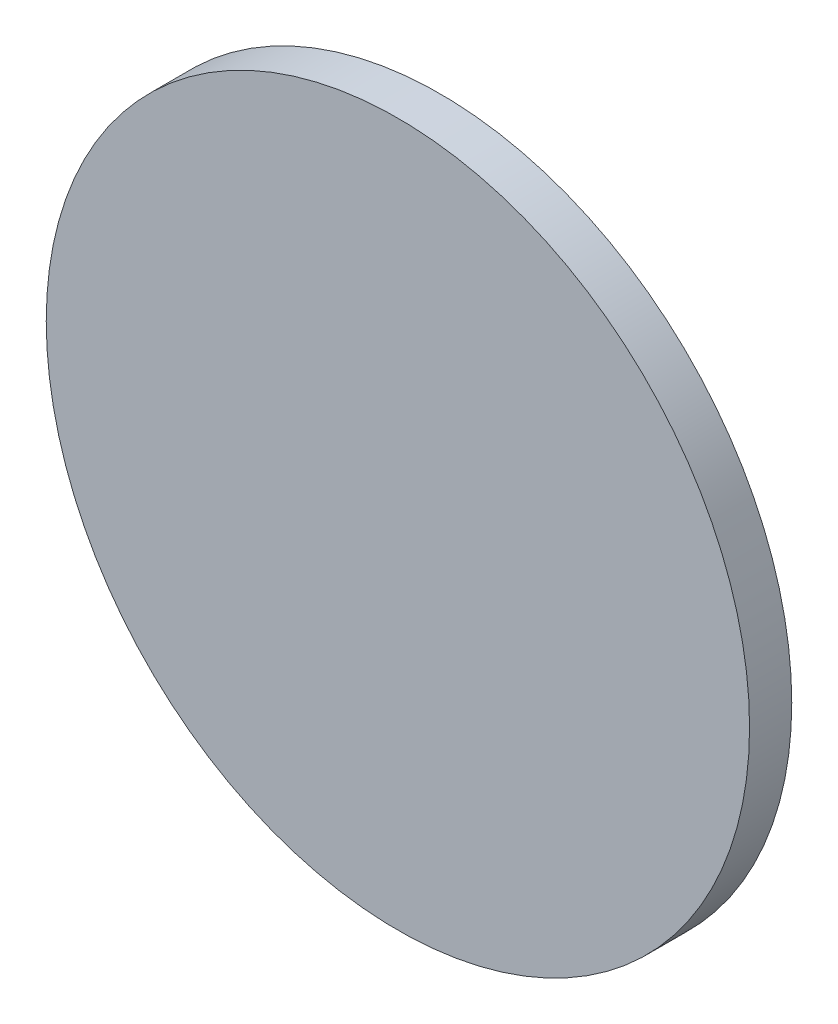
SolidWorks part; units mm, degrees
ref_plane "Plan de face" through (0, 0, 0) normal (0, 0, 1) x (1, 0, 0)
ref_plane "Plan de dessus" through (0, 0, 0) normal (0, 1, 0) x (1, 0, 0)
ref_plane "Plan de droite" through (0, 0, 0) normal (1, 0, 0) x (0, 0, -1)
sketch "Esquisse1" plane through (0, 0, 0) normal (0, 0, 1) x (1, 0, 0)
  circle A0 centre (0, 0) radius 25
  dimension "D1" = 50
extrude "Boss.-Extru.1" add sketch "Esquisse1" along normal blind 3
